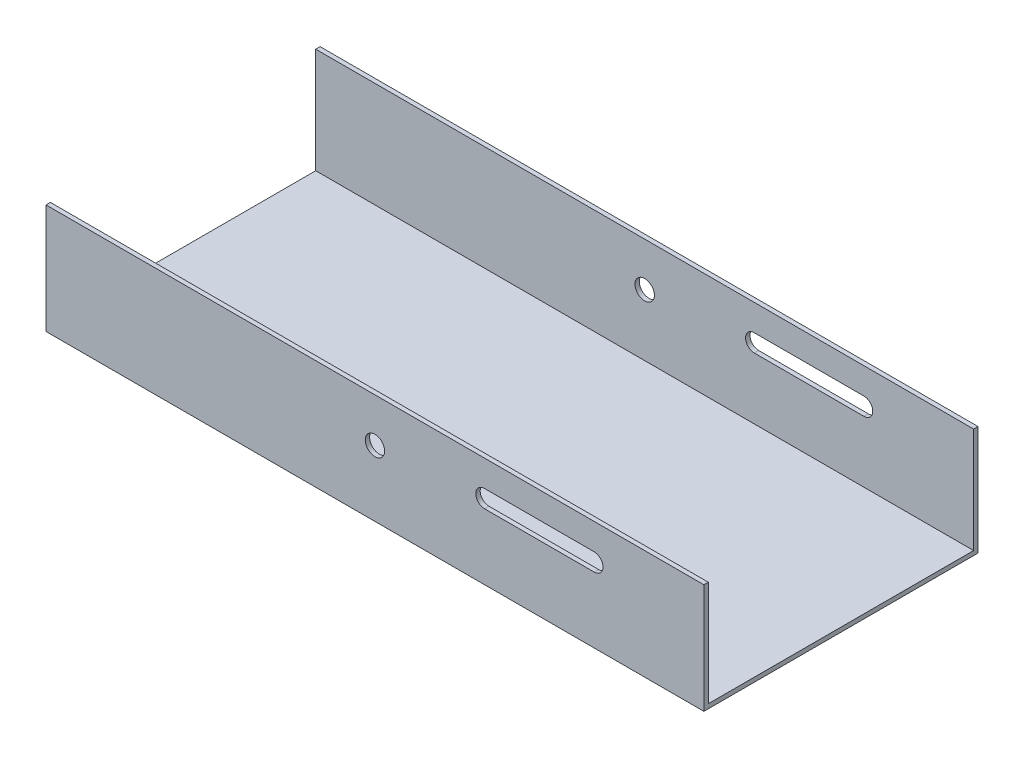
SolidWorks part; units mm, degrees
ref_plane "Front Plane" through (0, 0, 0) normal (0, 0, 1) x (1, 0, 0)
ref_plane "Top Plane" through (0, 0, 0) normal (0, 1, 0) x (1, 0, 0)
ref_plane "Right Plane" through (0, 0, 0) normal (1, 0, 0) x (0, 0, -1)
sketch "Sketch1" plane through (0, 0, 0) normal (0, 1, 0) x (1, 0, 0)
  line L1 (0, 0) -> (-300, 0)
  line L2 (0, 0) -> (0, 125)
  line L3 (0, 125) -> (-300, 125)
  line L4 (-300, 0) -> (-300, 125)
  dimension "D1" = 300
  dimension "D2" = 125
extrude "Boss-Extrude1" add sketch "Sketch1" along normal blind 50
shell "Shell1" thickness 2
sketch "Sketch2" plane through (0, 0, 0) normal (0, 0, 1) x (1, 0, 0)
  line L0 (-100, 34) -> (-50, 34) construction
  line L1 (-100, 38) -> (-50, 38)
  line L2 (-100, 30) -> (-50, 30)
  line L3 (-300, 0) -> (0, 0) construction
  line L4 (0, 50) -> (0, 0) construction
  arc A0 (-100, 38) -> (-100, 30) centre (-100, 34) ccw
  arc A1 (-50, 30) -> (-50, 38) centre (-50, 34) ccw
  point P2 (-75, 34)
  dimension "D1" = 30
  dimension "D2" = 8
  dimension "D3" = 50
  dimension "D4" = 100
extrude "Cut-Extrude1" cut sketch "Sketch2" against normal blind 142
sketch "Sketch3" plane through (0, 0, 0) normal (0, 0, 1) x (1, 0, 0)
  line L0 (0, 50) -> (0, 0) construction
  line L1 (-300, 0) -> (0, 0) construction
  circle A0 centre (-150, 30) radius 4.4238
  dimension "D1" = 150
  dimension "D2" = 30
extrude "Cut-Extrude2" cut sketch "Sketch3" against normal blind 132
sketch "Sketch4" plane through (0, 0, 0) normal (0, -1, 0) x (-1, 0, 0)
  line L0 (0, 125) -> (300, 125) construction
  line L1 (0, 0) -> (160.3221, 0)
  line L2 (0, 0) -> (0, 125)
  line L3 (0, 125) -> (160.3221, 125)
  line L4 (160.3221, 0) -> (160.3221, 125)
  line L5 (0, 95) -> (112.2506, 95)
  line L6 (0, 62.5) -> (112.2506, 62.5)
  line L7 (0, 33.5981) -> (112.2506, 33.5981)
  dimension "D1" = 30
  dimension "D2" = 33.5981
